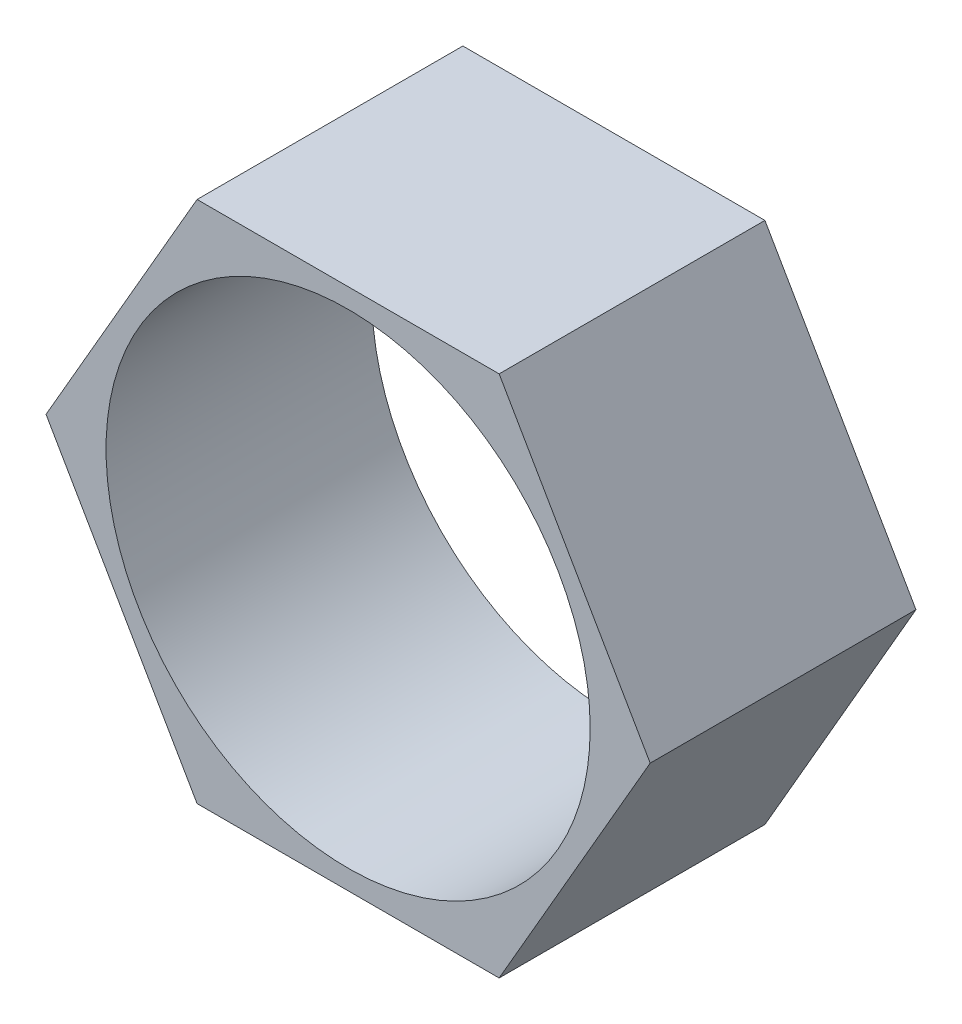
SolidWorks part; units mm, degrees
ref_plane "Front Plane" through (0, 0, 0) normal (0, 0, 1) x (1, 0, 0)
ref_plane "Top Plane" through (0, 0, 0) normal (0, 1, 0) x (1, 0, 0)
ref_plane "Right Plane" through (0, 0, 0) normal (1, 0, 0) x (0, 0, -1)
sketch "Sketch1" plane through (0, 0, 0) normal (0, 0, 1) x (1, 0, 0)
  line L1 (-10.6202, 11.5831) -> (-17.8371, -0.9169)
  line L2 (-17.8371, -0.9169) -> (-10.6202, -13.4169)
  line L3 (-10.6202, -13.4169) -> (3.8136, -13.4169)
  line L4 (3.8136, -13.4169) -> (11.0304, -0.9169)
  line L5 (11.0304, -0.9169) -> (3.8136, 11.5831)
  line L6 (3.8136, 11.5831) -> (-10.6202, 11.5831)
  circle A0 centre (-3.4033, -0.9169) radius 12.5 construction
  point P1 (-17.9585, -0.9169)
  dimension "D1" = 25
extrude "Boss-Extrude1" add sketch "Sketch1" along normal blind 12.7
sketch "Sketch2" plane through (0, 0, 12.7) normal (0, 0, 1) x (1, 0, 0)
  circle A0 centre (-3.4033, -0.9169) radius 11.3665 construction
  circle A1 centre (-3.4033, -0.9169) radius 11.3665 construction
  circle A2 centre (-3.4033, -0.9169) radius 11.5665
  dimension "D1" = 0.2
extrude "Cut-Extrude1" cut sketch "Sketch2" against normal blind 12.7
